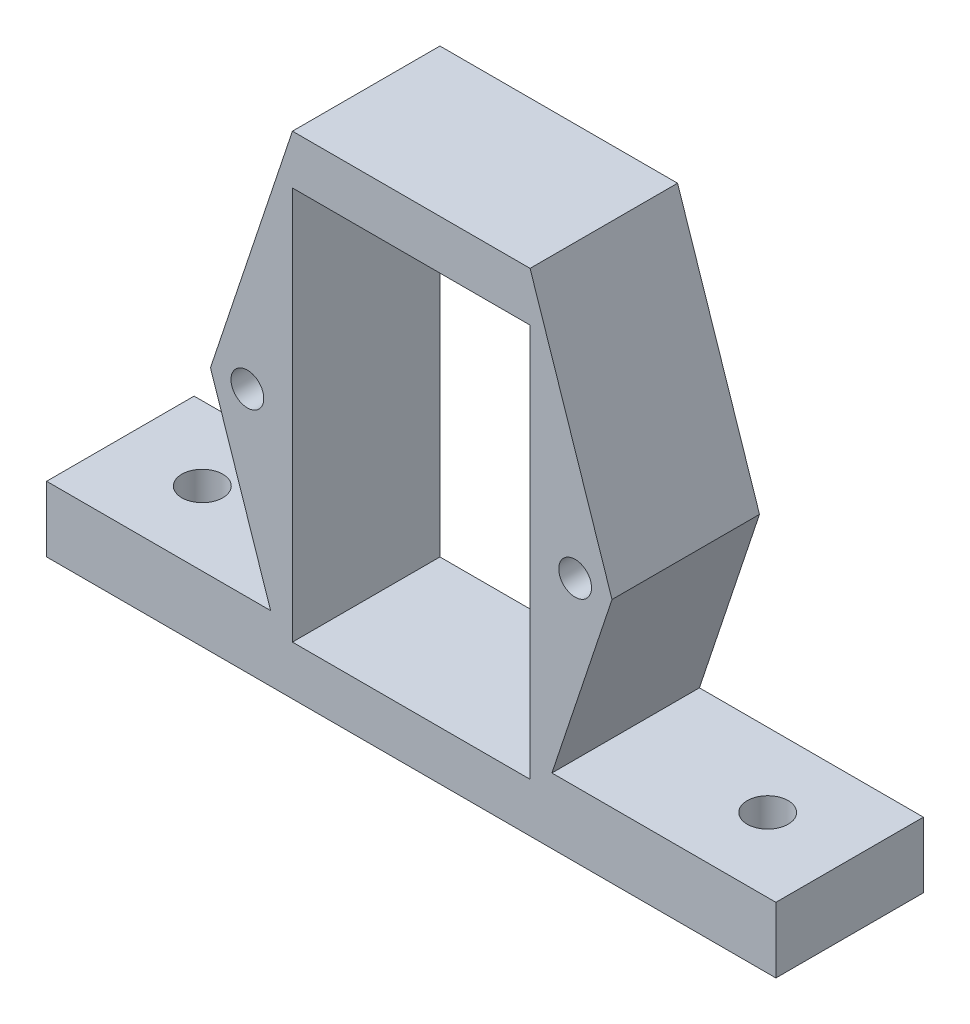
SolidWorks part; units mm, degrees
ref_plane "前视基准面" through (0, 0, 0) normal (0, 0, 1) x (1, 0, 0)
ref_plane "上视基准面" through (0, 0, 0) normal (0, 1, 0) x (1, 0, 0)
ref_plane "右视基准面" through (0, 0, 0) normal (1, 0, 0) x (0, 0, -1)
sketch "草图1" plane through (0, 0, 0) normal (0, 0, 1) x (1, 0, 0)
  line L0 (-36.6976, 27.4588) -> (12.3024, -32.5412) construction
  line L1 (-36.6976, 27.4588) -> (12.3024, 27.4588)
  line L2 (-36.6976, 27.4588) -> (-36.6976, -32.5412)
  line L3 (-36.6976, -32.5412) -> (12.3024, -32.5412)
  line L4 (12.3024, 27.4588) -> (12.3024, -32.5412)
  line L5 (-32.1976, -2.5412) -> (7.8024, -2.5412)
  line L6 (-26.6976, 21.4588) -> (2.3024, 21.4588)
  line L7 (-26.6976, 21.4588) -> (-26.6976, -26.5412)
  line L8 (-26.6976, -26.5412) -> (2.3024, -26.5412)
  line L9 (2.3024, 21.4588) -> (2.3024, -26.5412)
  line L10 (-26.6976, 21.4588) -> (2.3024, -26.5412) construction
  line L11 (-26.6976, -26.5412) -> (2.3024, 21.4588) construction
  line L12 (-26.6976, -32.5412) -> (2.3024, -32.5412)
  line L13 (-26.6976, 27.4588) -> (-36.6976, -2.5412)
  line L14 (-36.6976, -2.5412) -> (-26.6976, -32.5412)
  line L15 (2.3024, 27.4588) -> (12.3024, -2.5412)
  line L16 (12.3024, -2.5412) -> (2.3024, -32.5412)
  line L17 (-36.6976, -24.5412) -> (-29.3643, -24.5412)
  line L18 (-36.6976, -24.5412) -> (-56.6976, -24.5412)
  line L19 (-36.6976, -24.5412) -> (-36.6976, -32.5412)
  line L20 (-36.6976, -32.5412) -> (-56.6976, -32.5412)
  line L21 (-56.6976, -24.5412) -> (-56.6976, -32.5412)
  line L22 (12.3024, -24.5412) -> (32.3024, -24.5412)
  line L23 (12.3024, -24.5412) -> (12.3024, -32.5412)
  line L24 (12.3024, -32.5412) -> (32.3024, -32.5412)
  line L25 (32.3024, -24.5412) -> (32.3024, -32.5412)
  line L26 (12.3024, -24.5412) -> (4.9691, -24.5412)
  circle A0 centre (-32.1976, -2.5412) radius 2
  circle A1 centre (7.8024, -2.5412) radius 2
  point P4 (-12.1976, -2.5412)
  point P12 (-12.1976, -2.5412)
  point P14 (2.3024, 27.4588)
  point P17 (-12.1976, -32.5412)
  point P18 (-26.6976, 27.4588)
  point P23 (12.3024, -24.5412)
  point P24 (-36.6976, -24.5412)
  dimension "D6" = 29
  dimension "D1" = 60
  dimension "D2" = 49
  dimension "D3" = 29
  dimension "D4" = 48
  dimension "D5" = 40
  dimension "D7" = 8
  dimension "D8" = 8
  dimension "D9" = 20
  dimension "D10" = 20
extrude "凸台-拉伸2" add sketch "草图1" along normal blind 18
sketch "草图2" plane through (0, -24.5412, 0) normal (0, 1, 0) x (1, 0, 0)
  line L0 (-56.6976, -9) -> (-46.6976, -9) construction
  line L1 (-56.6976, -18) -> (-56.6976, 0) construction
  line L2 (32.3024, -9) -> (22.3024, -9) construction
  line L3 (32.3024, -18) -> (32.3024, 0) construction
  circle A0 centre (-46.6976, -9) radius 2.5
  circle A1 centre (22.3024, -9) radius 2.5
  point P10 (15.0394, -15.8654)
  dimension "D2" = 10
  dimension "D1" = 10
extrude "切除-拉伸1" cut sketch "草图2" against normal blind 18
